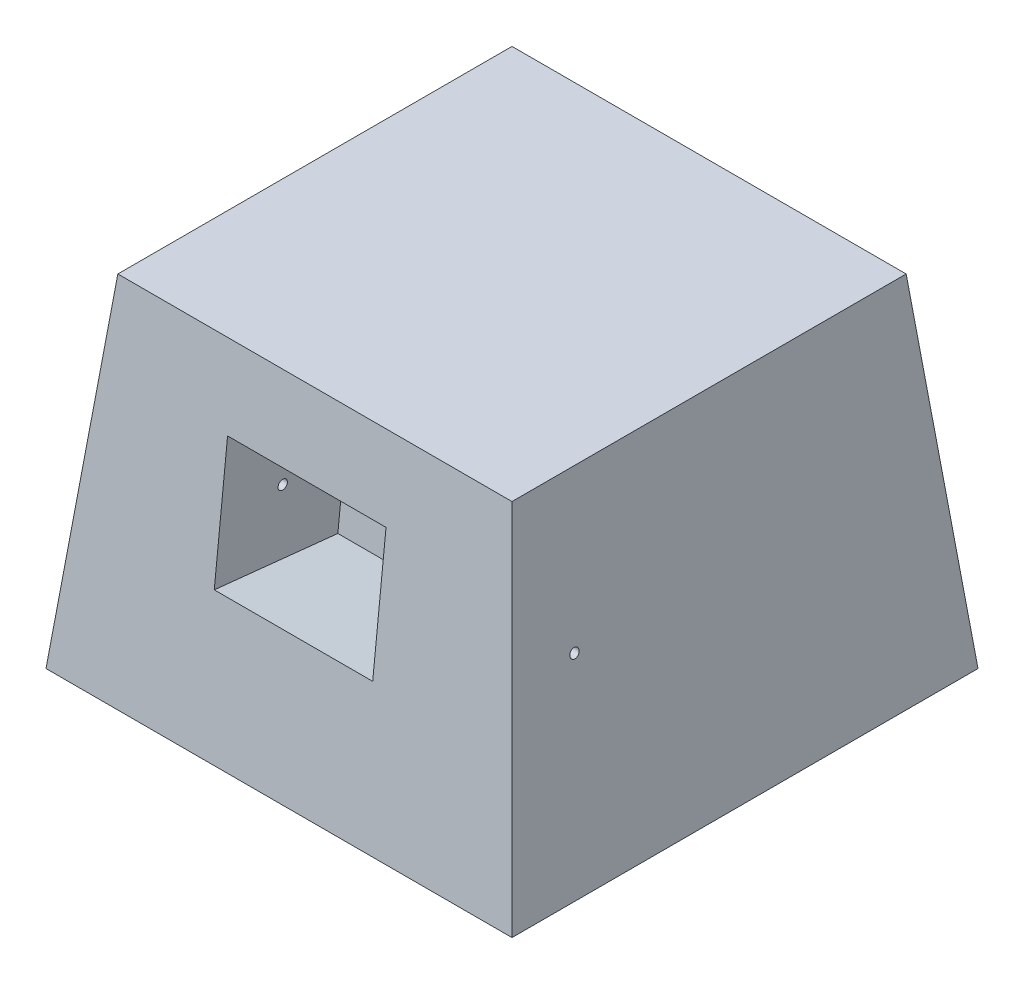
SolidWorks part; units mm, degrees
ref_plane "Front Plane" through (0, 0, 0) normal (0, 0, 1) x (1, 0, 0)
ref_plane "Top Plane" through (0, 0, 0) normal (0, 1, 0) x (1, 0, 0)
ref_plane "Right Plane" through (0, 0, 0) normal (1, 0, 0) x (0, 0, -1)
sketch "Sketch1" plane through (0, 0, 0) normal (0, 1, 0) x (1, 0, 0)
  line L1 (-75, -75) -> (75, -75)
  line L2 (-75, -75) -> (-75, 75)
  line L3 (-75, 75) -> (75, 75)
  line L4 (75, -75) -> (75, 75)
  line L5 (-75, -75) -> (75, 75) construction
  line L6 (-75, 75) -> (75, -75) construction
  point P0 (0, 0)
  dimension "D3" = 150
  dimension "D1" = 150
  dimension "D2" = 150
extrude "Boss-Extrude1" add sketch "Sketch1" along normal blind 110 draft 6 contours L3 L4 L1 L2
sketch "Sketch12" plane through (0, 7.7967, -74.1805) normal (0, 0.1045, -0.9945) x (-1, 0, 0)
  line L0 (-63.4385, 102.7663) -> (63.4385, 102.7663)
  line L1 (63.4385, 102.7663) -> (75, -7.8396)
  line L2 (75, -7.8396) -> (-75, -7.8396)
  line L3 (-75, -7.8396) -> (-63.4385, 102.7663)
  dimension "D1" = 150
  dimension "D2" = 111.2085
  dimension "D3" = 126.8771
sketch "Sketch14" plane through (0, 7.7967, 74.1805) normal (0, 0.1045, 0.9945) x (1, 0, 0)
  line L1 (-25.5, 36.7663) -> (25.5, 36.7663)
  line L2 (-25.5, 36.7663) -> (-25.5, 77.7663)
  line L3 (-25.5, 77.7663) -> (25.5, 77.7663)
  line L4 (25.5, 36.7663) -> (25.5, 77.7663)
  line L5 (-25.5, 36.7663) -> (25.5, 77.7663) construction
  line L6 (-25.5, 77.7663) -> (25.5, 36.7663) construction
  line L7 (-63.4385, 102.7663) -> (63.4385, 102.7663) construction
  line L8 (63.4385, 102.7663) -> (0, 102.7663) construction
  line L9 (0, 102.7663) -> (0, -8.3293) construction
  point P0 (0, 57.2663)
  point P9 (0, 77.7663)
  point P16 (0, 59.765)
  point P17 (0, 66.475)
  point P18 (0, 0)
  point P19 (0, 65.7295)
  dimension "D1" = 51
  dimension "D2" = 41
  dimension "D3" = 25
extrude "Cut-Extrude2" cut sketch "Sketch14" against normal blind 40
sketch "Sketch22" plane through (0, 0, 0) normal (0, -1, 0) x (1, 0, 0)
  line L0 (75, -75) -> (-75, -75)
  line L1 (-75, -75) -> (-75, 75)
  line L2 (-75, 75) -> (75, 75)
  line L3 (75, 75) -> (75, -75)
sketch "Sketch23" plane through (-25.5, 0, 0) normal (1, 0, 0) x (0, 0, -1)
  line L0 (-66.0517, 85.137) -> (-70.3374, 44.3616) construction
  line L1 (-68.1946, 64.7493) -> (-28.4137, 60.5681) construction
  line L2 (-26.2709, 80.9558) -> (-30.5565, 40.1804) construction
  circle A0 centre (-48.3041, 62.6587) radius 1.5
  dimension "D1" = 3
  dimension "D2" = 20
extrude "Cut-Extrude3" cut sketch "Sketch23" against normal through all both and the other way through all
sketch "Sketch24" plane through (74.1805, 7.7967, 0) normal (0.9945, 0.1045, 0) x (0, 0, -1)
  line L0 (-63.4385, 102.7663) -> (-75, -7.8396)
  line L1 (-75, -7.8396) -> (75, -7.8396)
  line L2 (75, -7.8396) -> (63.4385, 102.7663)
  line L3 (63.4385, 102.7663) -> (-63.4385, 102.7663)
  circle A0 centre (-48.3041, 55.1642) radius 1.5
